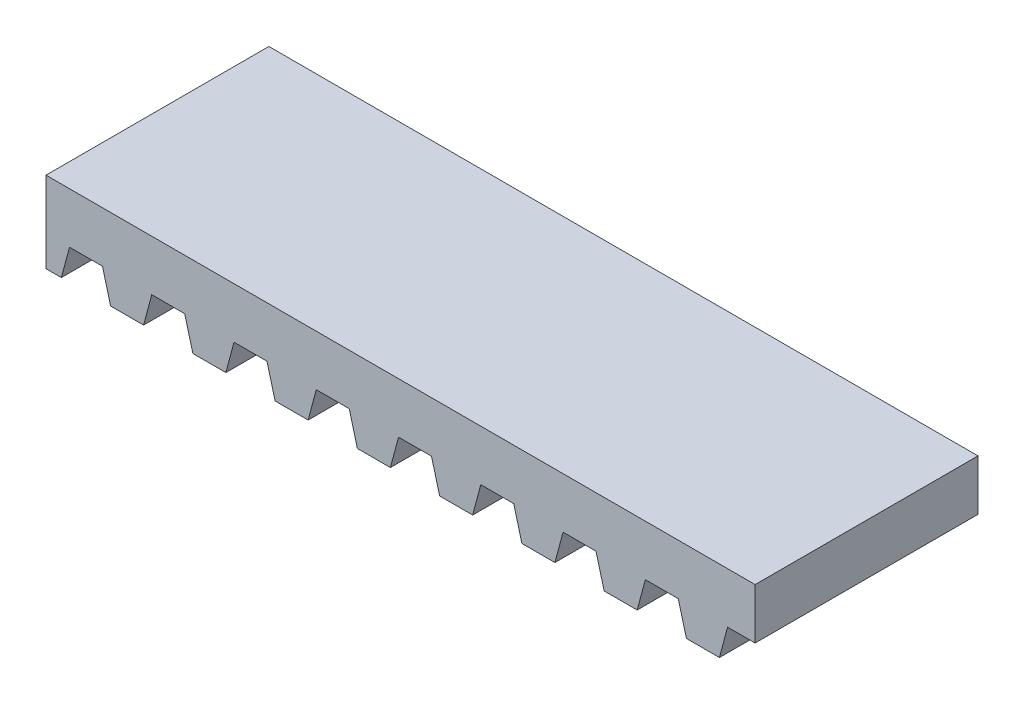
SolidWorks part; units mm, degrees
ref_plane "前基準面" through (0, 0, 0) normal (0, 0, 1) x (1, 0, 0)
ref_plane "上基準面" through (0, 0, 0) normal (0, 1, 0) x (1, 0, 0)
ref_plane "右基準面" through (0, 0, 0) normal (1, 0, 0) x (0, 0, -1)
sketch "草圖1" plane through (0, 0, 0) normal (0, 0, 1) x (1, 0, 0)
  line L1 (-32.2215, 9.8485) -> (37.7785, 9.8485)
  line L2 (-32.2215, 9.8485) -> (-32.2215, 4.8485)
  line L3 (-32.2215, 4.8485) -> (37.7785, 4.8485)
  line L4 (37.7785, 9.8485) -> (37.7785, 4.8485)
  dimension "D1" = 5
  dimension "D2" = 70
extrude "填料-伸長1" add sketch "草圖1" along normal blind 22
sketch "草圖2" plane through (0, 0, 22) normal (0, 0, 1) x (1, 0, 0)
  line L0 (-22.5851, 1.8485) -> (-21.7812, 4.8485)
  line L1 (-32.2215, 4.8485) -> (37.7785, 4.8485)
  line L2 (-32.2215, 4.8485) -> (-32.2215, 1.8485)
  line L3 (-32.2215, 1.8485) -> (37.7785, 1.8485)
  line L4 (37.7785, 4.8485) -> (37.7785, 1.8485)
  line L5 (-17.7242, 1.8485) -> (-18.5281, 4.8485)
  line L7 (-14.4651, 1.8485) -> (-13.6612, 4.8485)
  line L8 (-30.7051, 1.8485) -> (-29.9012, 4.8485)
  line L9 (-9.6042, 1.8485) -> (-10.4081, 4.8485)
  line L10 (-25.8442, 1.8485) -> (-26.6481, 4.8485)
  line L11 (-6.3451, 1.8485) -> (-5.5412, 4.8485)
  line L12 (-1.4842, 1.8485) -> (-2.2881, 4.8485)
  line L13 (1.7749, 1.8485) -> (2.5788, 4.8485)
  line L14 (6.6358, 1.8485) -> (5.8319, 4.8485)
  line L15 (9.8949, 1.8485) -> (10.6988, 4.8485)
  line L16 (14.7558, 1.8485) -> (13.9519, 4.8485)
  line L17 (18.0149, 1.8485) -> (18.8188, 4.8485)
  line L18 (22.8758, 1.8485) -> (22.0719, 4.8485)
  line L19 (26.1349, 1.8485) -> (26.9388, 4.8485)
  line L20 (30.9958, 1.8485) -> (30.1919, 4.8485)
  line L21 (34.2549, 1.8485) -> (35.0588, 4.8485)
  line L25 (42.3749, 1.8485) -> (43.1788, 4.8485) [skipped]
  line L26 (47.2358, 1.8485) -> (46.4319, 4.8485) [skipped]
  line L27 (39.1158, 1.8485) -> (38.3119, 4.8485) [skipped]
  line M12 (-32.2215, 4.8485) -> (37.7785, 4.8485)
  dimension "D1" = 70
  dimension "D2" = 3
  dimension "D3" = 10
extrude "填料-伸長2" add sketch "草圖2" against normal blind 10 contours L3 L8 L2 M12 | L10 L3 L0 M12 | L3 L7 L1 L5 | L3 L11 L1 L9 | L3 L13 L1 L12 | L3 L15 L1 L14 | L3 L17 L1 L16 | L3 L19 L1 L18 | L3 L21 L1 L20
sketch "草圖3" plane through (0, 0, 0) normal (0, 0, -1) x (-1, 0, 0)
  line L0 (32.2215, 4.8485) -> (-37.7785, 4.8485) construction
  line L1 (-37.7785, 4.8485) -> (-37.7785, 9.8485) construction
  line L2 (32.2215, 9.8485) -> (32.2215, 4.8485) construction
  circle A0 centre (-32.7785, 7.3485) radius 1.7
  circle A1 centre (-2.7785, 7.3485) radius 1.7
  circle A2 centre (27.2215, 7.3485) radius 1.7
  dimension "D7" = 3.4
  dimension "D8" = 3.4
  dimension "D9" = 3.4
  dimension "D1" = 2.5
  dimension "D2" = 2.5
  dimension "D3" = 2.5
  dimension "D4" = 5
  dimension "D5" = 5
  dimension "D6" = 30
extrude "除料-伸長1" cut sketch "草圖3" against normal blind 8
sketch "草圖5" plane through (-32.2215, 0, 0) normal (-1, 0, 0) x (0, 0, 1)
  line L0 (22, 9.8485) -> (22, 1.8485) construction
  line L1 (0, 9.8485) -> (0, 4.8485) construction
  line L2 (22, 9.8485) -> (0, 9.8485) construction
  circle A0 centre (10, 7.3485) radius 1.7
  circle A1 centre (18, 7.3485) radius 1.7
  dimension "D3" = 3.4
  dimension "D4" = 3.4
  dimension "D1" = 4
  dimension "D2" = 10
  dimension "D5" = 2.5
  dimension "D6" = 2.5
extrude "除料-伸長2" cut sketch "草圖5" against normal blind 8
equation "\"ㄓ\"=8.9282"
